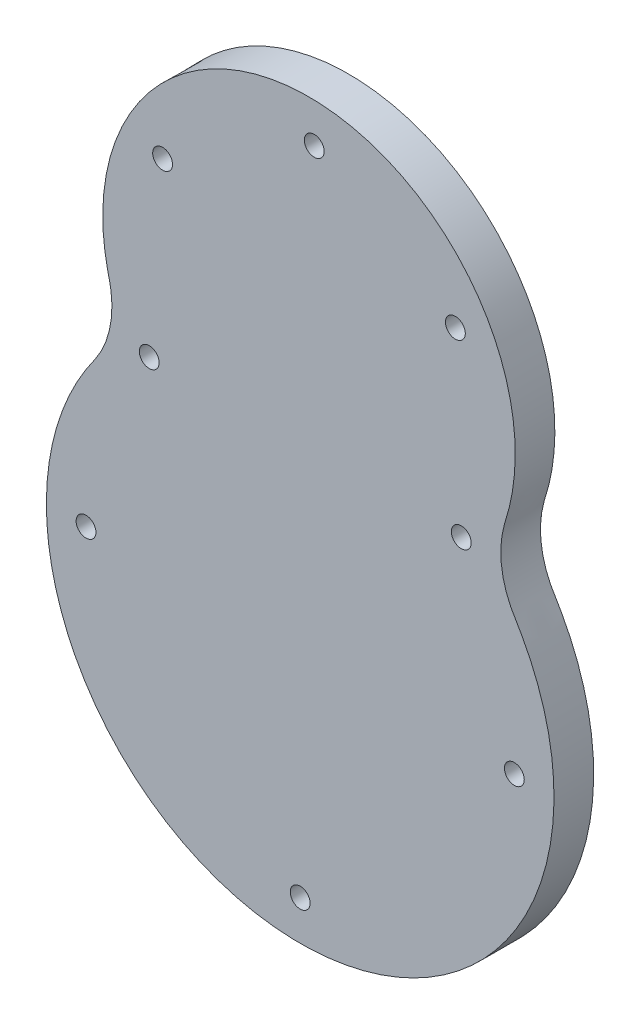
SolidWorks part; units mm, degrees
ref_plane "Front Plane" through (0, 0, 0) normal (0, 0, 1) x (1, 0, 0)
ref_plane "Top Plane" through (0, 0, 0) normal (0, 1, 0) x (1, 0, 0)
ref_plane "Right Plane" through (0, 0, 0) normal (1, 0, 0) x (0, 0, -1)
sketch "Sketch2" plane through (0, 0, 0) normal (0, 0, 1) x (1, 0, 0)
  line L0 (0, 0) -> (1.1084, 34.9824) construction
  circle A0 centre (0, 0) radius 32 construction
  circle A1 centre (1.1084, 34.9824) radius 26 construction
  arc A2 (-24.0993, 28.6129) -> (-25.9881, 18.6713) centre (-35.7337, 25.673) cw construction
  arc A3 (25.8623, 27.0299) -> (27.118, 16.9887) centre (37.2872, 23.3595) ccw construction
  arc A4 (-24.0993, 28.6129) -> (25.8623, 27.0299) centre (1.1084, 34.9824) cw construction
  arc A5 (-25.9881, 18.6713) -> (27.118, 16.9887) centre (0, 0) ccw construction
  arc A6 (-21.9275, 15.7539) -> (22.8808, 14.3342) centre (0, 0) ccw construction
  arc A7 (21.1019, 28.5592) -> (22.8808, 14.3342) centre (37.2872, 23.3595) ccw construction
  arc A8 (-19.2517, 29.8378) -> (21.1019, 28.5592) centre (1.1084, 34.9824) cw construction
  arc A9 (-19.2517, 29.8378) -> (-21.9275, 15.7539) centre (-35.7337, 25.673) cw construction
  spline S0 degree 3 poles (-24.624, 31.2618) (-27.1195, 48.5206) (-15.4978, 61.5216) (1.9317, 60.9694) (19.3612, 60.4172) (30.1366, 46.7065) (26.5536, 29.6404) (26.4325, 29.0635) (26.1511, 27.9181) (25.5904, 26.229) (25.3942, 25.0634) (25.3393, 24.4765) (25.1759, 22.7293) (25.3937, 20.9879) (25.9823, 19.3347) (26.1813, 18.7757) (26.6623, 17.6872) (27.6284, 16.1781) (28.1996, 15.1373) (28.4705, 14.6093) (40.9608, -9.7316) (26.3315, -32.8503) (-1.0134, -31.984) (-28.3582, -31.1176) (-41.4947, -7.1192) (-27.4885, 16.3823) (-27.1848, 16.892) (-26.5489, 17.8946) (-25.4891, 19.3395) (-24.9402, 20.3954) (-24.7062, 20.9407) (-24.0141, 22.5533) (-23.6866, 24.2774) (-23.739, 26.0315) (-23.7566, 26.6207) (-23.8787, 27.7964) (-24.3313, 29.5175) (-24.5397, 30.6785) (-24.624, 31.2618) (-27.1195, 48.5206) (-15.4978, 61.5216) knots -0.007979 0 0 0 0.179794 0.179794 0.179794 0.359588 0.359588 0.359588 0.367566 0.375545 0.383523 0.383523 0.383523 0.406905 0.406905 0.406905 0.414937 0.422969 0.431001 0.431001 0.431001 0.679794 0.679794 0.679794 0.928586 0.928586 0.928586 0.936618 0.944651 0.952683 0.952683 0.952683 0.976064 0.976064 0.976064 0.984043 0.992021 1 1 1 1.179794 1.179794 1.179794 weights 1 0.761671 0.761671 1 0.761671 0.761671 1 1 1 1 1 1 0.984275 0.984275 1 1 1 1 1 1 0.671798 0.671798 1 0.671798 0.671798 1 1 1 1 1 1 0.984275 0.984275 1 1 1 1 1 1 0.761671 0.761671 only from (-24.624, 31.2618) to (-24.624, 31.2618)
  point P22 (1.7734, 55.9719)
  point P25 (27, 0)
  point P26 (-27, 0)
  point P27 (-19.0324, 22.5)
  point P28 (-17.3483, 45)
  point P29 (20.3089, 22.5)
  point P30 (20.3089, 22.5)
  point P31 (19.565, 45)
  dimension "D1" = 35
  dimension "D2" = 64
  dimension "D3" = 52
  dimension "D4" = 12
  dimension "D5" = 21
  dimension "D6" = 22.5
  dimension "D7" = 45
extrude "Boss-Extrude1" add sketch "Sketch2" against normal blind 5
hole_wizard "M3 Tapped Hole1" positions "Sketch3" profile "Sketch4" tap size "M3" standard "ISO" end condition through all
sketch "Sketch3" plane through (0, 0, 0) normal (0, 0, 1) x (1, 0, 0)
  arc A0 (21.1019, 28.5592) -> (-19.2517, 29.8378) centre (1.1084, 34.9824) ccw construction
  arc A1 (-21.9275, 15.7539) -> (22.8808, 14.3342) centre (0, 0) ccw construction
  arc A2 (-21.9275, 15.7539) -> (-19.2517, 29.8378) centre (-35.7337, 25.673) ccw construction
  point P0 (1.7734, 55.9719)
  point P5 (19.565, 45)
  point P8 (20.3089, 22.5)
  point P11 (27, 0)
  point P14 (0, -27)
  point P19 (-27, 0)
  point P22 (-19.0324, 22.5)
  point P27 (-17.3483, 45)
sketch "Sketch4" plane through (1.7734, 55.9719, 0) normal (1, 0, 0) x (0, -1, 0)
  line L0 (0, 0) -> (0, 5)
  line L1 (0, 5) -> (1.25, 5)
  line L2 (1.25, 5) -> (1.25, 0)
  line L5 (1.25, 0) -> (0, 0)
  line L11 (0, -6.35) -> (0, 107.95) construction
  dimension "Thru Tap Drill Dia." = 2.5
  dimension "Thru Tap Drill Depth" = 5
cosmetic thread "Hole Thread1" parameters "D2"=3
cosmetic thread "Hole Thread2" parameters "D2"=3
cosmetic thread "Hole Thread3" parameters "D2"=3
cosmetic thread "Hole Thread4" parameters "D2"=3
cosmetic thread "Hole Thread5" parameters "D2"=3
cosmetic thread "Hole Thread6" parameters "D2"=3
cosmetic thread "Hole Thread7" parameters "D2"=3
cosmetic thread "Hole Thread8" parameters "D2"=3
